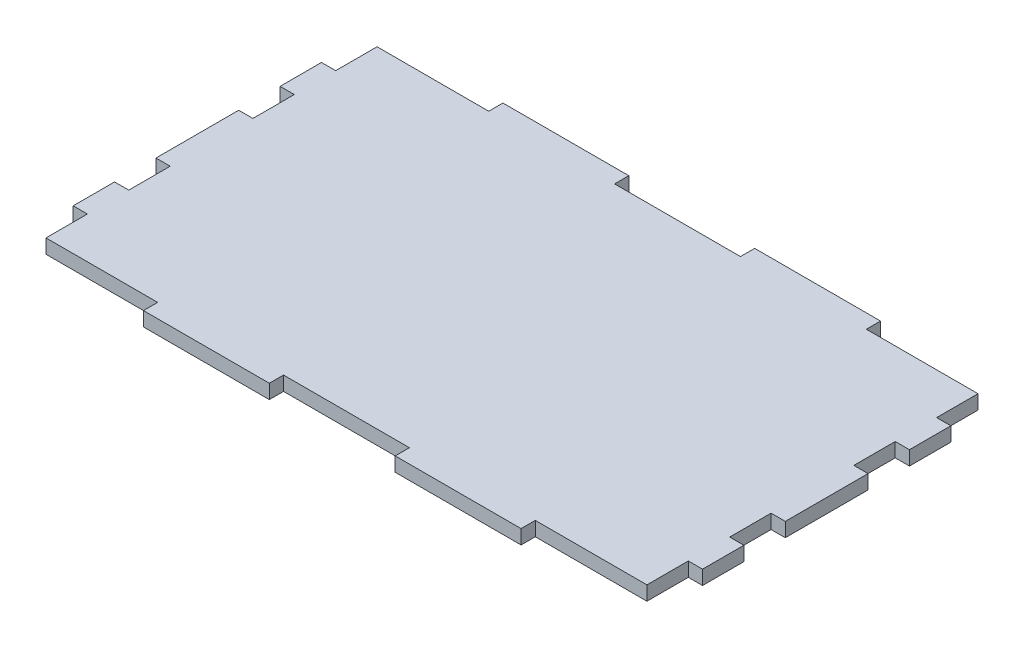
SolidWorks part; units mm, degrees
ref_plane "Front Plane" through (0, 0, 0) normal (0, 0, 1) x (1, 0, 0)
ref_plane "Top Plane" through (0, 0, 0) normal (0, 1, 0) x (1, 0, 0)
ref_plane "Right Plane" through (0, 0, 0) normal (1, 0, 0) x (0, 0, -1)
sketch "Sketch1" plane through (0, 0, 0) normal (0, 1, 0) x (1, 0, 0)
  line L1 (-214.3598, 36.9171) -> (154.7657, 36.9171)
  line L2 (-214.3598, 36.9171) -> (-214.3598, -173.9283)
  line L3 (-214.3598, -173.9283) -> (154.7657, -173.9283)
  line L4 (154.7657, 36.9171) -> (154.7657, -173.9283)
  dimension "D1" = 369.1255
  dimension "D2" = 210.8454
extrude "Boss-Extrude1" add sketch "Sketch1" along normal blind 8.3312
sketch "Sketch2" plane through (0, 8.3312, 0) normal (0, 1, 0) x (1, 0, 0)
  line L0 (-29.797, 36.9171) -> (-29.797, -173.9283) construction
  line L1 (154.7657, 36.9171) -> (-214.3598, 36.9171) construction
  line L2 (-214.3598, -173.9283) -> (154.7657, -173.9283) construction
  line L3 (-214.3598, -68.5056) -> (154.7657, -68.5056) construction
  line L4 (-214.3598, 36.9171) -> (-214.3598, -173.9283) construction
  line L5 (154.7657, -173.9283) -> (154.7657, 36.9171) construction
  line L6 (7.1155, 28.5859) -> (-66.7096, 28.5859)
  line L7 (7.1155, -173.9283) -> (-66.7096, -173.9283)
  line L8 (-29.797, -173.9283) -> (-29.797, -165.5971)
  line L9 (7.1155, -165.5971) -> (-66.7096, -165.5971)
  line L10 (-66.7096, -173.9283) -> (-66.7096, -165.5971)
  line L11 (-66.7096, -173.9283) -> (-140.5347, -173.9283)
  line L12 (-66.7096, -173.9283) -> (-66.7096, -165.5971)
  line L14 (-140.5347, -173.9283) -> (-140.5347, -165.5971)
  line L15 (-140.5347, -173.9283) -> (-214.3598, -173.9283)
  line L16 (-140.5347, -173.9283) -> (-140.5347, -165.5971)
  line L17 (-140.5347, -165.5971) -> (-214.3598, -165.5971)
  line L18 (-214.3598, -173.9283) -> (-214.3598, -165.5971)
  line L19 (-214.3598, -165.5971) -> (-206.0286, -165.5971)
  line L20 (-214.3598, -165.5971) -> (-214.3598, -141.3242)
  line L21 (-214.3598, -141.3242) -> (-206.0286, -141.3242)
  line L22 (-206.0286, -165.5971) -> (-206.0286, -141.3242)
  line L23 (-214.3598, -92.7784) -> (-206.0286, -92.7784)
  line L24 (-214.3598, -92.7784) -> (-214.3598, -117.0513)
  line L25 (-214.3598, -117.0513) -> (-206.0286, -117.0513)
  line L26 (-206.0286, -92.7784) -> (-206.0286, -117.0513)
  line L27 (-66.7096, 36.9171) -> (-66.7096, 28.5859)
  line L28 (7.1155, 36.9171) -> (-66.7096, 36.9171)
  line L29 (-29.797, 36.9171) -> (-29.797, 28.5859)
  line L30 (-140.5347, 28.5859) -> (-214.3598, 28.5859)
  line L31 (-214.3598, 36.9171) -> (-214.3598, 28.5859)
  line L32 (-140.5347, 36.9171) -> (-214.3598, 36.9171)
  line L33 (-140.5347, 36.9171) -> (-140.5347, 28.5859)
  line L34 (-214.3598, 4.3131) -> (-206.0286, 4.3131)
  line L35 (-206.0286, 28.5859) -> (-206.0286, 4.3131)
  line L36 (-214.3598, 28.5859) -> (-206.0286, 28.5859)
  line L37 (-214.3598, 28.5859) -> (-214.3598, 4.3131)
  line L38 (-214.3598, -19.9598) -> (-206.0286, -19.9598)
  line L39 (-206.0286, -44.2327) -> (-206.0286, -19.9598)
  line L40 (-214.3598, -44.2327) -> (-206.0286, -44.2327)
  line L41 (-214.3598, -44.2327) -> (-214.3598, -19.9598)
  line L42 (7.1155, -173.9283) -> (7.1155, -165.5971)
  line L43 (80.9406, -165.5971) -> (154.7657, -165.5971)
  line L44 (154.7657, -173.9283) -> (154.7657, -165.5971)
  line L45 (80.9406, -173.9283) -> (154.7657, -173.9283)
  line L46 (80.9406, -173.9283) -> (80.9406, -165.5971)
  line L47 (154.7657, -141.3242) -> (146.4345, -141.3242)
  line L48 (146.4345, -165.5971) -> (146.4345, -141.3242)
  line L49 (154.7657, -165.5971) -> (146.4345, -165.5971)
  line L50 (154.7657, -165.5971) -> (154.7657, -141.3242)
  line L51 (154.7657, -117.0513) -> (146.4345, -117.0513)
  line L52 (146.4345, -92.7784) -> (146.4345, -117.0513)
  line L53 (154.7657, -92.7784) -> (146.4345, -92.7784)
  line L54 (154.7657, -92.7784) -> (154.7657, -117.0513)
  line L55 (154.7657, -44.2327) -> (154.7657, -19.9598)
  line L56 (154.7657, -44.2327) -> (146.4345, -44.2327)
  line L57 (146.4345, -44.2327) -> (146.4345, -19.9598)
  line L58 (154.7657, -19.9598) -> (146.4345, -19.9598)
  line L59 (154.7657, 28.5859) -> (146.4345, 28.5859)
  line L60 (146.4345, 28.5859) -> (146.4345, 4.3131)
  line L61 (154.7657, 4.3131) -> (146.4345, 4.3131)
  line L62 (154.7657, 28.5859) -> (154.7657, 4.3131)
  line L63 (80.9406, 28.5859) -> (154.7657, 28.5859)
  line L64 (80.9406, 36.9171) -> (80.9406, 28.5859)
  line L65 (80.9406, 36.9171) -> (154.7657, 36.9171)
  line L66 (154.7657, 36.9171) -> (154.7657, 28.5859)
  line L67 (7.1155, 36.9171) -> (7.1155, 28.5859)
  point P26 (-29.797, -68.5056)
  line M1 (-214.3598, 36.9171) -> (-214.3598, -173.9283)
  line M2 (-214.3598, -173.9283) -> (154.7657, -173.9283)
  dimension "D1" = 8.3312
  dimension "D2" = 8.3312
  dimension "D3" = 73.8251
  dimension "D4" = 36.9125
  dimension "D5" = 73.8251
  dimension "D6" = 8.3312
  dimension "D7" = 8.3312
  dimension "D8" = 24.2729
  dimension "D9" = 24.2729
  dimension "D10" = 24.2729
  dimension "D11" = 24.2729
extrude "Cut-Extrude1" cut sketch "Sketch2" against normal through all contours L26 L23 L25 M1 | L17 L22 L21 M1 | L14 L17 M1 M2 | L7 L42 L9 L8 | L10 L8 L9 M2 | L44 L45 L46 L43 | L50 L47 L48 L49 | L51 L52 L53 L54 | L55 L58 L57 L56 | L59 L60 L61 L62 | L66 L65 L64 L63 | L28 L27 L6 L67 | L38 L39 L40 L41 | L37 L34 L35 L36 | L31 L32 L33 L30
equation "\"D1@Sketch1\"=\"Base Length@Assembled Container.Assembly\""
equation "\"D2@Sketch1\"=\"Base Width@Assembled Container.Assembly\""
equation "\"D1@Boss-Extrude1\"=\"Acrylic Thickness@Assembled Container.Assembly\""
equation "\"D1@Sketch2\"=\"Acrylic Thickness@Assembled Container.Assembly\""
equation "\"D2@Sketch2\"=\"Acrylic Thickness@Assembled Container.Assembly\""
equation "\"D4@Sketch2\"=\"Lid Long Side Inner Cutout@Assembled Container.Assembly\""
equation "\"D3@Sketch2\"=\"Lid Long Side Outer Cutout@Assembled Container.Assembly\""
equation "\"D6@Sketch2\"=\"Acrylic Thickness@Assembled Container.Assembly\""
equation "\"D7@Sketch2\"=\"Acrylic Thickness@Assembled Container.Assembly\""
equation "\"D8@Sketch2\"=\"Lid Short Side Outer Cutout@Assembled Container.Assembly\""
equation "\"D9@Sketch2\"=\"Lid Short Side Outer Overhang@Assembled Container.Assembly\""
equation "\"D10@Sketch2\"=\"Lid Short Side Middle Cutout@Assembled Container.Assembly\""
